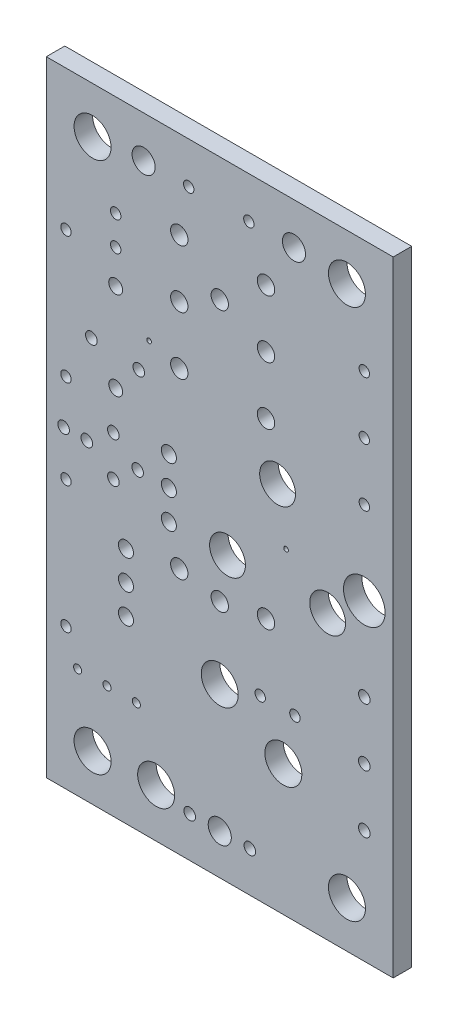
SolidWorks part; units mm, degrees
ref_plane "Plan de face" through (0, 0, 0) normal (0, 0, 1) x (1, 0, 0)
ref_plane "Plan de dessus" through (0, 0, 0) normal (0, 1, 0) x (1, 0, 0)
ref_plane "Plan de droite" through (0, 0, 0) normal (1, 0, 0) x (0, 0, -1)
sketch "Model" plane through (0, 0, 0) normal (0, 0, 1) x (1, 0, 0)
  line L1 (0, 54) -> (30, 54)
  line L2 (0, 54) -> (0, 0)
  line L3 (0, 0) -> (30, 0)
  line L4 (30, 54) -> (30, 0)
  line L278 (-4.4605, 0) -> (53.8292, 0) construction
  line L279 (0, -5.5056) -> (0, 76.3648) construction
  line L280 (30, -5.5056) -> (30, 76.3648) construction
  line L281 (-4.4605, 54) -> (53.8292, 54) construction
  line L282 (39.5217, 27) -> (47.7353, 27) construction
  line L283 (15, 64.7069) -> (15, 73.1854) construction
  line L284 (-4.6426, 50) -> (5.2388, 50) construction
  line L285 (4, 58.758) -> (4, 46.99) construction
  circle A0 centre (5.7988, 28.7503) radius 0.5
  circle A1 centre (6.8898, 18.0492) radius 0.65
  circle A2 centre (10.6007, 27.0002) radius 0.65
  circle A3 centre (1.7005, 30.8991) radius 0.45
  circle A4 centre (19.0005, 41.4007) radius 0.75
  circle A5 centre (5.7988, 25.2503) radius 0.5
  circle A6 centre (7.8988, 27.0003) radius 0.5
  circle A7 centre (3.4988, 27.0003) radius 0.5
  circle A8 centre (1.4988, 27.0003) radius 0.5
  circle A9 centre (10.6007, 29.5402) radius 0.65
  circle A10 centre (15, 20.6997) radius 0.75
  circle A11 centre (15, 43.2997) radius 0.75
  circle A12 centre (19.0005, 46.4007) radius 0.75
  circle A13 centre (11.5005, 36.4007) radius 0.75
  circle A14 centre (11.5005, 41.4007) radius 0.75
  circle A15 centre (11.5005, 46.4007) radius 0.75
  circle A16 centre (27.4993, 39.2011) radius 0.45
  circle A17 centre (27.4993, 34.2011) radius 0.45
  circle A18 centre (27.5006, 27.0006) radius 1.8
  circle A19 centre (5.9995, 39.8094) radius 0.6
  circle A20 centre (24.3306, 24.5006) radius 1.55
  circle A21 centre (27.5006, 19.8006) radius 0.5
  circle A22 centre (7.7889, 9.4996) radius 0.35
  circle A23 centre (2.7089, 9.4996) radius 0.35
  circle A24 centre (15.6706, 24.5006) radius 1.55
  circle A25 centre (27.5006, 9.7993) radius 0.5
  circle A26 centre (6.8898, 15.5092) radius 0.65
  circle A27 centre (20.0006, 32.0006) radius 1.55
  circle A28 centre (12.3171, 50.4165) radius 0.45
  circle A29 centre (21.4171, 50.4165) radius 1
  circle A30 centre (8.4171, 50.4165) radius 1
  circle A33 centre (1.7005, 12.1996) radius 0.45
  circle A34 centre (20.4991, 11.303) radius 1.6
  circle A35 centre (14.9987, 14.5021) radius 1.6
  circle A36 centre (9.4996, 4.2024) radius 1.6
  circle A45 centre (6.8898, 20.5892) radius 0.65
  circle A55 centre (10.6007, 24.4602) radius 0.65
  circle A61 centre (1.7005, 23.2004) radius 0.45
  circle A62 centre (27.5006, 14.8006) radius 0.5
  circle A79 centre (20.7366, 27.4828) radius 0.2
  circle A80 centre (8.8951, 37.1653) radius 0.2
  circle A94 centre (6.0033, 45.2679) radius 0.45
  circle A99 centre (1.7005, 41.8998) radius 0.45
  circle A100 centre (19.0005, 36.4007) radius 0.75
  circle A111 centre (27.4993, 44.2011) radius 0.45
  circle A112 centre (5.9995, 32.1894) radius 0.6
  circle A120 centre (19.0005, 21.3995) radius 0.75
  circle A151 centre (5.2489, 9.4996) radius 0.35
  circle A152 centre (21.4998, 15.4) radius 0.45
  circle A154 centre (6.0033, 42.7279) radius 0.45
  circle A169 centre (17.5171, 50.4165) radius 0.45
  circle A172 centre (3.8976, 34.8818) radius 0.5
  circle A177 centre (7.9959, 34.5542) radius 0.5
  circle A180 centre (18.5001, 15.4) radius 0.45
  circle A191 centre (11.4998, 21.3995) radius 0.75
  circle A192 centre (4, 50) radius 1.6
  circle A193 centre (26, 50) radius 1.6
  circle A194 centre (26, 4) radius 1.6
  circle A195 centre (4, 4) radius 1.6
  circle A196 centre (12.4003, 3.5001) radius 0.5
  circle A197 centre (15.0003, 3.5001) radius 1
  circle A198 centre (17.6003, 3.5001) radius 0.5
  circle A199 centre (5.7988, 27.0003) radius 0.5 [skipped]
  circle A200 centre (20.0006, 24.5006) radius 1.55 [skipped]
  dimension "D7" = 2
  dimension "D8" = 2
  dimension "D10" = 2
  dimension "D11" = 3
  dimension "D12" = 3
  dimension "D13" = 2
  dimension "D15" = 3
  dimension "D17" = 3
  dimension "D18" = 3
  dimension "D19" = 2
  dimension "D20" = 2
  dimension "D1" = 15
  dimension "D2" = 30
  dimension "D3" = 54
  dimension "D4" = 27
  dimension "D5" = 4
  dimension "D6" = 4
  dimension "D9" = 2
  dimension "D14" = 2
  dimension "D16" = 2
extrude "Boss.-Extru.1" add sketch "Model" along normal blind 1.6
